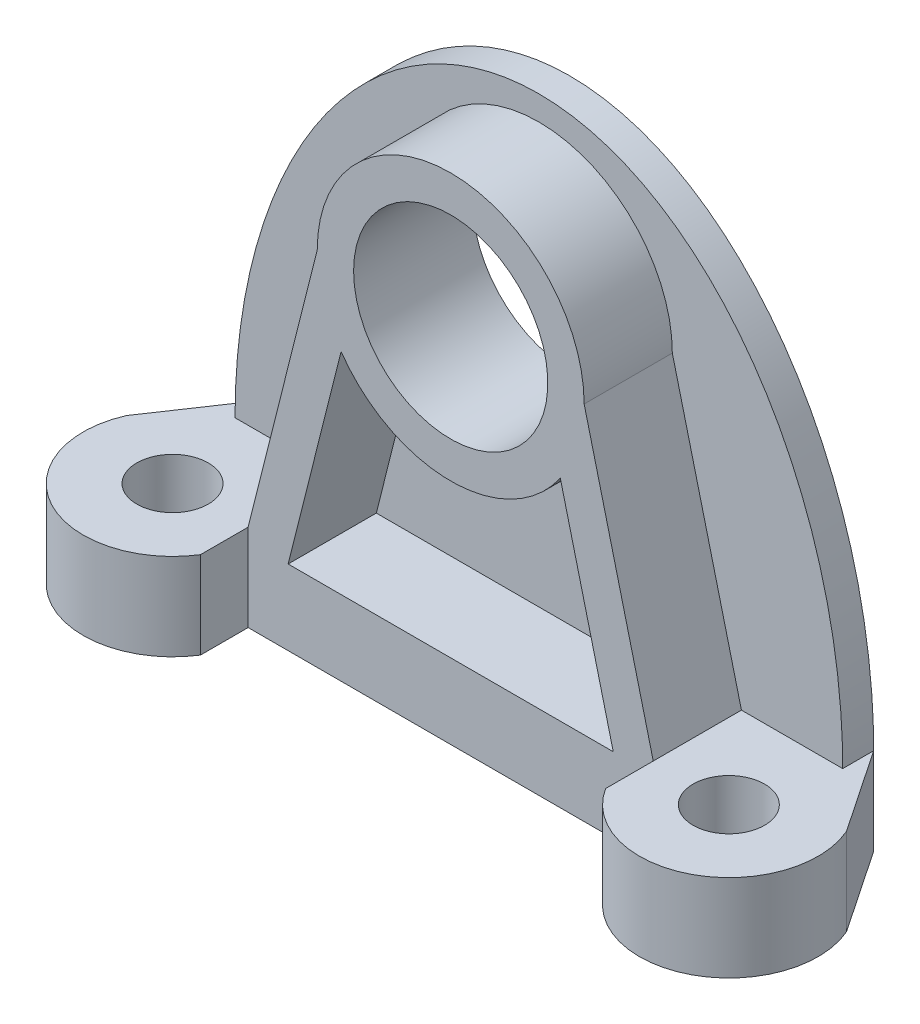
SolidWorks part; units mm, degrees
ref_plane "Alzado" through (0, 0, 0) normal (0, 0, 1) x (1, 0, 0)
ref_plane "Planta" through (0, 0, 0) normal (0, 1, 0) x (1, 0, 0)
ref_plane "Vista lateral" through (0, 0, 0) normal (1, 0, 0) x (0, 0, -1)
sketch "Croquis2" plane through (0, 0, 0) normal (0, 1, 0) x (1, 0, 0)
  line L0 (-25.5, 0) -> (25.5, 0)
  line L1 (25.5, 0) -> (30.2182, -7)
  line L2 (17, -14) -> (17, -10)
  line L3 (17, -10) -> (-17, -10)
  line L4 (0, 0) -> (0, -10) construction
  line L5 (30.2182, -7) -> (0, -7) construction
  line L6 (-17, -14) -> (-17, -10)
  line L7 (-25.5, 0) -> (-30.2182, -7)
  arc A0 (30.2182, -7) -> (17, -14) centre (23.3443, -10) cw
  circle A1 centre (23.3443, -10) radius 3
  circle A2 centre (-23.3443, -10) radius 3
  arc A3 (-30.2182, -7) -> (-17, -14) centre (-23.3443, -10) ccw
  dimension "D2" = 7.5
  dimension "D6" = 6
  dimension "D1" = 17
  dimension "D3" = 25.5
  dimension "D4" = 10
  dimension "D5" = 4
  dimension "D7" = 3
extrude "Saliente-Extruir1" add sketch "Croquis2" along normal blind 7.3
sketch "Croquis3" plane through (0, 0, 10) normal (0, 0, 1) x (1, 0, 0)
  line L0 (17, 7.3) -> (17, 0) construction
  line L1 (-17, 7.3) -> (17, 7.3)
  line L2 (-17, 7.3) -> (-17, 6.3)
  line L3 (-17, 6.3) -> (17, 6.3)
  line L4 (17, 7.3) -> (17, 6.3)
  dimension "D1" = 1
extrude "Cortar-Extruir1" cut sketch "Croquis3" against normal blind 7.4
sketch "Croquis5" plane through (0, 0, 0) normal (0, 0, -1) x (-1, 0, 0)
  line L0 (-25.5, 7.3) -> (25.5, 7.3) construction
  line L1 (-25.5, 7.3) -> (25.5, 7.3)
  circle A0 centre (0, 30.35) radius 8.15
  ellipse E0 centre (0, 7.3) end of major axis (0, -29) minor radius 25.5 (-25.5, 7.3) -> (25.5, 7.3) cw
  dimension "D2" = 16.3
  dimension "D1" = 43.6
  dimension "D3" = 13.25
extrude "Saliente-Extruir3" add sketch "Croquis5" against normal up to surface (2.6 mm away) up to face at (0, 6.8, 2.6)
sketch "Croquis6" plane through (0, 0, 2.6) normal (0, 0, 1) x (1, 0, 0)
  line L0 (17, 6.3) -> (17, 7.3)
  line L1 (17, 7.3) -> (11.2, 30.35)
  line L2 (13.6425, 6.3) -> (9.1987, 23.9606)
  line L3 (-17, 6.3) -> (17, 6.3) construction
  line L4 (-17, 6.3) -> (-17, 7.3)
  line L5 (-17, 7.3) -> (-11.2, 30.35)
  line L6 (-13.6425, 6.3) -> (-9.1987, 23.9606)
  line L7 (-17, 6.3) -> (-13.6425, 6.3)
  line L8 (17, 6.3) -> (13.6425, 6.3)
  circle A0 centre (0, 30.35) radius 8.15
  arc A1 (-9.1987, 23.9606) -> (9.1987, 23.9606) centre (0, 30.35) ccw
  arc A2 (11.2, 30.35) -> (-11.2, 30.35) centre (0, 30.35) ccw
  dimension "D1" = 16.3
  dimension "D2" = 22.4
  dimension "D3" = 3.5
  dimension "D4" = 3.5
extrude "Saliente-Extruir4" add sketch "Croquis6" along normal up to surface (7.4 mm away) up to face at (0, 3.15, 10)
sketch "Croquis7" plane through (0, 0, 0) normal (0, 1, 0) x (1, 0, 0)
  line L0 (-23.3443, -13) -> (-23.3443, -7) construction
  line L1 (23.3443, -13) -> (23.3443, -7) construction
  circle A0 centre (-23.3443, -10) radius 3 construction
  circle A1 centre (23.3443, -10) radius 3 construction
